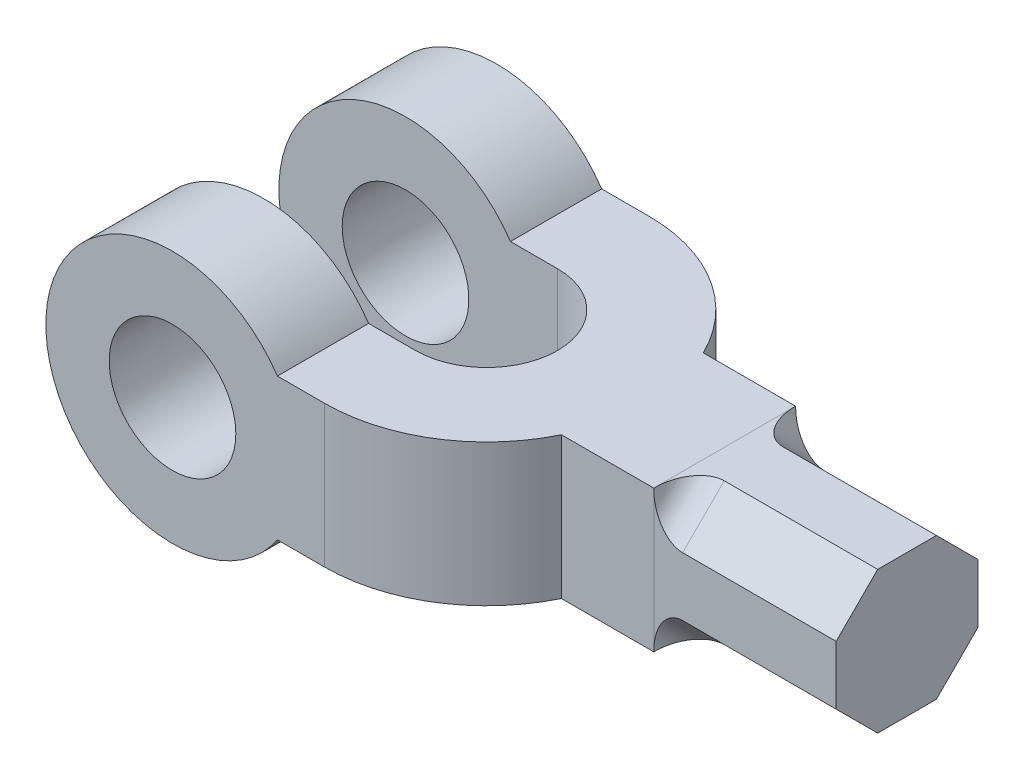
SolidWorks part; units mm, degrees
ref_plane "Front Plane" through (0, 0, 0) normal (0, 0, 1) x (1, 0, 0)
ref_plane "Top Plane" through (0, 0, 0) normal (0, 1, 0) x (1, 0, 0)
ref_plane "Right Plane" through (0, 0, 0) normal (1, 0, 0) x (0, 0, -1)
sketch "Croquis1" plane through (0, 0, 0) normal (0, 0, 1) x (1, 0, 0)
  line L1 (20.7123, -14) -> (30, -14)
  line L3 (20.7123, 14) -> (30, 14)
  line L4 (30, -14) -> (30, 14)
  arc A0 (20.7123, 14) -> (20.7123, -14) centre (0, 0) ccw
  circle A1 centre (0, 0) radius 12.5
  point P4 (25, 0)
  point P9 (0, 0)
  dimension "D1" = 50
  dimension "D2" = 25
  dimension "D3" = 28
  dimension "D4" = 30
extrude "Saliente-Extruir2" add sketch "Croquis1" along normal mid plane 64
sketch "Croquis3" plane through (0, 0, 0) normal (0, 1, 0) x (1, 0, 0)
  line L0 (-25, 32) -> (-25, -32) construction
  line L1 (-80, -14) -> (30, -14)
  line L2 (-80, -14) -> (-80, 14)
  line L3 (-80, 14) -> (30, 14)
  line L4 (30, -14) -> (30, 14)
  line L5 (-80, -14) -> (30, 14) construction
  line L6 (-80, 14) -> (30, -14) construction
  line L7 (30, -32) -> (30, 32) construction
  point P0 (-25, 0)
  dimension "D1" = 28
extrude "Cortar-Extruir1" cut sketch "Croquis3" against normal mid plane 64
sketch "Croquis7" plane through (0, 14, 0) normal (0, 1, 0) x (1, 0, 0)
  line L0 (30, 32) -> (30, 14)
  line L1 (30, -32) -> (30, -14)
  arc A0 (30, 14) -> (30, -14) centre (30, 0) cw
  arc A1 (30, 32) -> (30, -32) centre (30, 0) cw
  dimension "D1" = 14
  dimension "D2" = 18
extrude "Saliente-Extruir3" add sketch "Croquis7" against normal blind 28
sketch "Croquis9" plane through (0, 0, 0) normal (0, 1, 0) x (1, 0, 0)
  line L1 (47, -14) -> (77, -14)
  line L2 (47, -14) -> (47, 14)
  line L3 (47, 14) -> (77, 14)
  line L4 (77, -14) -> (77, 14)
  line L5 (47, -14) -> (77, 14) construction
  line L6 (47, 14) -> (77, -14) construction
  arc A0 (30, -32) -> (30, 32) centre (30, 0) ccw construction
  point P0 (62, 0)
  dimension "D1" = 28
  dimension "D2" = 15
extrude "Saliente-Extruir4" add sketch "Croquis9" along normal mid plane 28
sketch "Croquis10" plane through (77, 0, 0) normal (1, 0, 0) x (0, 0, -1)
  line L1 (-14.0002, 5.7986) -> (-13.9998, -5.7994)
  line L2 (-13.9998, -5.7994) -> (-5.7986, -14.0002)
  line L3 (-5.7986, -14.0002) -> (5.7994, -13.9998)
  line L4 (5.7994, -13.9998) -> (14.0002, -5.7986)
  line L5 (14.0002, -5.7986) -> (13.9998, 5.7994)
  line L6 (13.9998, 5.7994) -> (5.7986, 14.0002)
  line L7 (5.7986, 14.0002) -> (-5.7994, 13.9998)
  line L8 (-5.7994, 13.9998) -> (-14.0002, 5.7986)
  circle A0 centre (0, 0) radius 14 construction
  point P1 (0, 0)
extrude "Saliente-Extruir5" add sketch "Croquis10" along normal blind 36
fillet "Redondeo2" radius 5.7 4 edges
